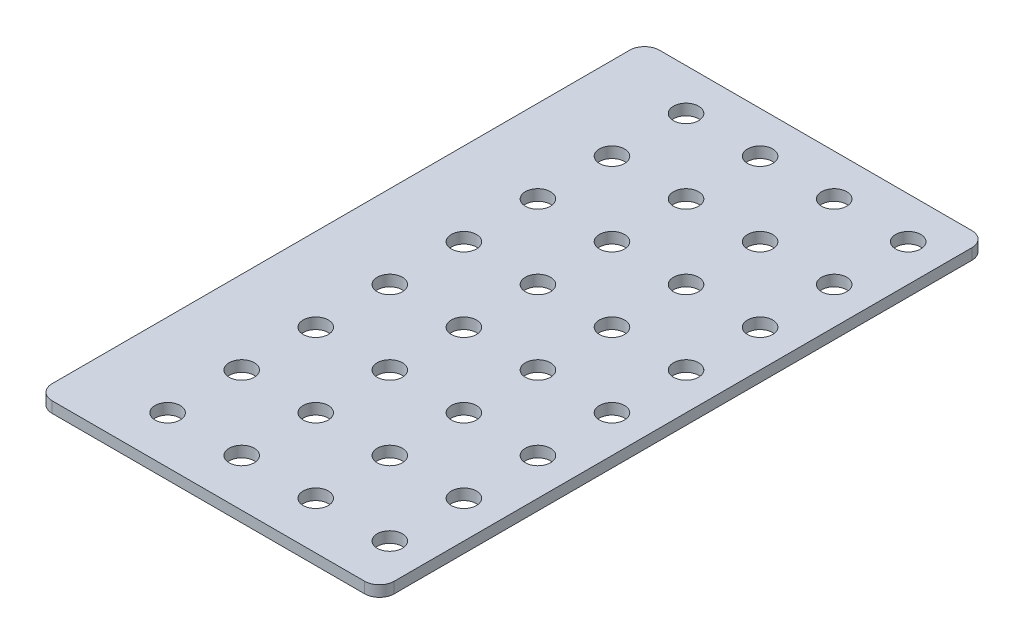
SolidWorks part; units mm, degrees
ref_plane "Front Plane" through (0, 0, 0) normal (0, 0, 1) x (1, 0, 0)
ref_plane "Top Plane" through (0, 0, 0) normal (0, 1, 0) x (1, 0, 0)
ref_plane "Right Plane" through (0, 0, 0) normal (1, 0, 0) x (0, 0, -1)
sketch "Sketch1" plane through (0, 0, 0) normal (0, 1, 0) x (1, 0, 0)
  line L0 (37.5, 89) -> (37.5, -116)
  line B0 (67, -116) -> (67, -131)
  line B1 (72, -136) -> (82, -136)
  line B2 (87, -131) -> (87, 104)
  line B3 (82, 109) -> (72, 109)
  line B4 (67, 104) -> (67, 89)
  line B5 (67, 89) -> (-73, 89)
  line B6 (-78, 84) -> (-78, -111)
  line B7 (-73, -116) -> (67, -116)
  circle B8 centre (-50, 75) radius 4.25
  circle B9 centre (-25, 75) radius 4.25
  circle B10 centre (0, 75) radius 4.25
  circle B11 centre (25, 75) radius 4.25
  circle B12 centre (50, 75) radius 4.25
  arc B13 (67, -131) -> (72, -136) centre (72, -131) ccw
  arc B14 (82, -136) -> (87, -131) centre (82, -131) ccw
  arc B15 (87, 104) -> (82, 109) centre (82, 104) ccw
  arc B16 (72, 109) -> (67, 104) centre (72, 104) ccw
  arc B17 (-73, 89) -> (-78, 84) centre (-73, 84) ccw
  arc B18 (-78, -111) -> (-73, -116) centre (-73, -111) ccw
  circle B19 centre (75, 75) radius 4.25
  circle B20 centre (-25, 50) radius 4.25
  circle B21 centre (0, 50) radius 4.25
  circle B22 centre (25, 50) radius 4.25
  circle B23 centre (50, 50) radius 4.25
  circle B24 centre (75, 50) radius 4.25
  circle B25 centre (-25, 25) radius 4.25
  circle B26 centre (0, 25) radius 4.25
  circle B27 centre (25, 25) radius 4.25
  circle B28 centre (50, 25) radius 4.25
  circle B29 centre (75, 25) radius 4.25
  circle B30 centre (-25, 0) radius 4.25
  circle B31 centre (0, 0) radius 4.25
  circle B32 centre (25, 0) radius 4.25
  circle B33 centre (50, 0) radius 4.25
  circle B34 centre (75, 0) radius 4.25
  circle B35 centre (-25, -25) radius 4.25
  circle B36 centre (0, -25) radius 4.25
  circle B37 centre (25, -25) radius 4.25
  circle B38 centre (50, -25) radius 4.25
  circle B39 centre (75, -25) radius 4.25
  circle B40 centre (-25, -50) radius 4.25
  circle B41 centre (0, -50) radius 4.25
  circle B42 centre (25, -50) radius 4.25
  circle B43 centre (50, -50) radius 4.25
  circle B44 centre (75, -50) radius 4.25
  circle B45 centre (-25, -75) radius 4.25
  circle B46 centre (0, -75) radius 4.25
  circle B47 centre (25, -75) radius 4.25
  circle B48 centre (50, -75) radius 4.25
  circle B49 centre (75, -75) radius 4.25
  circle B50 centre (-25, -100) radius 4.25
  circle B51 centre (0, -100) radius 4.25
  circle B52 centre (25, -100) radius 4.25
  circle B53 centre (50, -100) radius 4.25
  circle B54 centre (75, -100) radius 4.25
  circle B55 centre (-50, 50) radius 4.25
  circle B56 centre (-50, 25) radius 4.25
  circle B57 centre (-50, 0) radius 4.25
  circle B58 centre (-50, -25) radius 4.25
  circle B59 centre (-50, -50) radius 4.25
  circle B60 centre (-50, -75) radius 4.25
  circle B61 centre (-50, -100) radius 4.25
  dimension "D1" = 12.5
sketch_block_instance "Block-Extension Shim Block-1"
sketch_block "Block-Extension Shim Block" parameters "D1"=25, "D2"=25
extrude "Boss-Extrude1" add sketch "Sketch1" along normal blind 3.7 contours B6 B18 B7 L0 B5 B17 B61 B60 B59 B58 B57 B56 B55 B52 B51 B50 B47 B46 B45 B42 B41 B40 B37 B36 B35 B32 B31 B30
fillet "Fillet1" radius 5 2 edges at (37.5, 1.85, 116) (37.5, 1.85, -89)
